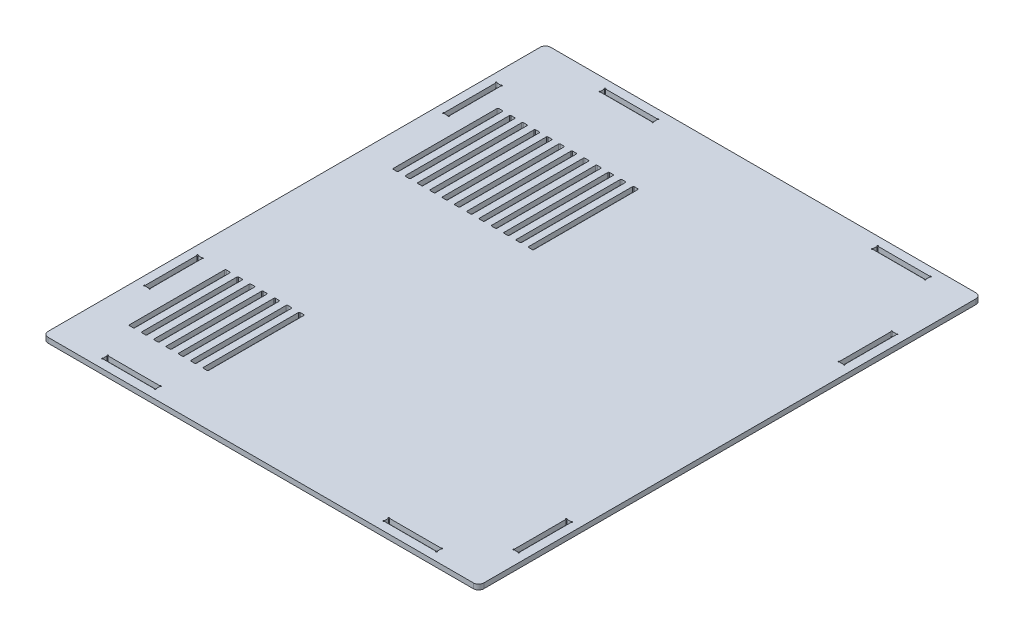
SolidWorks part; units mm, degrees
material "Acrylic (Medium-high impact)"
ref_plane "Front Plane" through (0, 0, 0) normal (0, 0, 1) x (1, 0, 0)
ref_plane "Top Plane" through (0, 0, 0) normal (0, 1, 0) x (1, 0, 0)
ref_plane "Right Plane" through (0, 0, 0) normal (1, 0, 0) x (0, 0, -1)
ref_plane "Plane1" through (0, 81.9, 0) normal (0, 1, 0) x (1, 0, 0)
sketch "Sketch1" plane through (0, 81.9, 0) normal (0, 1, 0) x (1, 0, 0)
  line L0 (-120.9, -142.9) -> (120.9, -142.9)
  line L1 (123.9, -139.9) -> (123.9, 139.9)
  line L2 (120.9, 142.9) -> (-120.9, 142.9)
  line L3 (-123.9, 139.9) -> (-123.9, -139.9)
  line L4 (-94.6875, -137.95) -> (-65.3125, -137.95)
  line L5 (-64.9625, -137.6) -> (-64.9625, -135.3)
  line L6 (-65.3125, -134.95) -> (-94.6875, -134.95)
  line L7 (-95.0375, -135.3) -> (-95.0375, -137.6)
  line L8 (65.3125, -137.95) -> (94.6875, -137.95)
  line L9 (95.0375, -137.6) -> (95.0375, -135.3)
  line L10 (94.6875, -134.95) -> (65.3125, -134.95)
  line L11 (64.9625, -135.3) -> (64.9625, -137.6)
  line L12 (-84.6875, 134.95) -> (-55.3125, 134.95)
  line L13 (-54.9625, 135.3) -> (-54.9625, 137.6)
  line L14 (-55.3125, 137.95) -> (-84.6875, 137.95)
  line L15 (-85.0375, 137.6) -> (-85.0375, 135.3)
  line L16 (70.3125, 134.95) -> (99.6875, 134.95)
  line L17 (100.0375, 135.3) -> (100.0375, 137.6)
  line L18 (99.6875, 137.95) -> (70.3125, 137.95)
  line L19 (69.9625, 137.6) -> (69.9625, 135.3)
  line L20 (116.3, -115.0375) -> (118.6, -115.0375)
  line L21 (118.95, -114.6875) -> (118.95, -85.3125)
  line L22 (118.6, -84.9625) -> (116.3, -84.9625)
  line L23 (115.95, -85.3125) -> (115.95, -114.6875)
  line L24 (116.3, 69.9625) -> (118.6, 69.9625)
  line L25 (118.95, 70.3125) -> (118.95, 99.6875)
  line L26 (118.6, 100.0375) -> (116.3, 100.0375)
  line L27 (115.95, 99.6875) -> (115.95, 70.3125)
  line L28 (-118.6, -90.0375) -> (-116.3, -90.0375)
  line L29 (-115.95, -89.6875) -> (-115.95, -60.3125)
  line L30 (-116.3, -59.9625) -> (-118.6, -59.9625)
  line L31 (-118.95, -60.3125) -> (-118.95, -89.6875)
  line L32 (-118.6, 79.9625) -> (-116.3, 79.9625)
  line L33 (-115.95, 80.3125) -> (-115.95, 109.6875)
  line L34 (-116.3, 110.0375) -> (-118.6, 110.0375)
  line L35 (-118.95, 109.6875) -> (-118.95, 80.3125)
  line L36 (-103.5, -114) -> (-101.5, -114)
  line L37 (-101, -113.5) -> (-101, -59.5)
  line L38 (-101.5, -59) -> (-103.5, -59)
  line L39 (-104, -59.5) -> (-104, -113.5)
  line L40 (-96.5, -114) -> (-94.5, -114)
  line L41 (-94, -113.5) -> (-94, -59.5)
  line L42 (-94.5, -59) -> (-96.5, -59)
  line L43 (-97, -59.5) -> (-97, -113.5)
  line L44 (-89.5, -114) -> (-87.5, -114)
  line L45 (-87, -113.5) -> (-87, -59.5)
  line L46 (-87.5, -59) -> (-89.5, -59)
  line L47 (-90, -59.5) -> (-90, -113.5)
  line L48 (-82.5, -114) -> (-80.5, -114)
  line L49 (-80, -113.5) -> (-80, -59.5)
  line L50 (-80.5, -59) -> (-82.5, -59)
  line L51 (-83, -59.5) -> (-83, -113.5)
  line L52 (-75.5, -114) -> (-73.5, -114)
  line L53 (-73, -113.5) -> (-73, -59.5)
  line L54 (-73.5, -59) -> (-75.5, -59)
  line L55 (-76, -59.5) -> (-76, -113.5)
  line L56 (-68.5, -114) -> (-66.5, -114)
  line L57 (-66, -113.5) -> (-66, -59.5)
  line L58 (-66.5, -59) -> (-68.5, -59)
  line L59 (-69, -59.5) -> (-69, -113.5)
  line L60 (-61.5, -114) -> (-59.5, -114)
  line L61 (-59, -113.5) -> (-59, -59.5)
  line L62 (-59.5, -59) -> (-61.5, -59)
  line L63 (-62, -59.5) -> (-62, -113.5)
  line L64 (-105.5, 38) -> (-103.5, 38)
  line L65 (-103, 38.5) -> (-103, 97.5)
  line L66 (-103.5, 98) -> (-105.5, 98)
  line L67 (-106, 97.5) -> (-106, 38.5)
  line L68 (-98.5, 38) -> (-96.5, 38)
  line L69 (-96, 38.5) -> (-96, 97.5)
  line L70 (-96.5, 98) -> (-98.5, 98)
  line L71 (-99, 97.5) -> (-99, 38.5)
  line L72 (-91.5, 38) -> (-89.5, 38)
  line L73 (-89, 38.5) -> (-89, 97.5)
  line L74 (-89.5, 98) -> (-91.5, 98)
  line L75 (-92, 97.5) -> (-92, 38.5)
  line L76 (-84.5, 38) -> (-82.5, 38)
  line L77 (-82, 38.5) -> (-82, 97.5)
  line L78 (-82.5, 98) -> (-84.5, 98)
  line L79 (-85, 97.5) -> (-85, 38.5)
  line L80 (-77.5, 38) -> (-75.5, 38)
  line L81 (-75, 38.5) -> (-75, 97.5)
  line L82 (-75.5, 98) -> (-77.5, 98)
  line L83 (-78, 97.5) -> (-78, 38.5)
  line L84 (-70.5, 38) -> (-68.5, 38)
  line L85 (-68, 38.5) -> (-68, 97.5)
  line L86 (-68.5, 98) -> (-70.5, 98)
  line L87 (-71, 97.5) -> (-71, 38.5)
  line L88 (-63.5, 38) -> (-61.5, 38)
  line L89 (-61, 38.5) -> (-61, 97.5)
  line L90 (-61.5, 98) -> (-63.5, 98)
  line L91 (-64, 97.5) -> (-64, 38.5)
  line L92 (-56.5, 38) -> (-54.5, 38)
  line L93 (-54, 38.5) -> (-54, 97.5)
  line L94 (-54.5, 98) -> (-56.5, 98)
  line L95 (-57, 97.5) -> (-57, 38.5)
  line L96 (-49.5, 38) -> (-47.5, 38)
  line L97 (-47, 38.5) -> (-47, 97.5)
  line L98 (-47.5, 98) -> (-49.5, 98)
  line L99 (-50, 97.5) -> (-50, 38.5)
  line L100 (-42.5, 38) -> (-40.5, 38)
  line L101 (-40, 38.5) -> (-40, 97.5)
  line L102 (-40.5, 98) -> (-42.5, 98)
  line L103 (-43, 97.5) -> (-43, 38.5)
  line L104 (-35.5, 38) -> (-33.5, 38)
  line L105 (-33, 38.5) -> (-33, 97.5)
  line L106 (-33.5, 98) -> (-35.5, 98)
  line L107 (-36, 97.5) -> (-36, 38.5)
  line L108 (-28.5, 38) -> (-26.5, 38)
  line L109 (-26, 38.5) -> (-26, 97.5)
  line L110 (-26.5, 98) -> (-28.5, 98)
  line L111 (-29, 97.5) -> (-29, 38.5)
  arc A0 (-123.9, -139.9) -> (-120.9, -142.9) centre (-120.9, -139.9) ccw
  arc A1 (120.9, -142.9) -> (123.9, -139.9) centre (120.9, -139.9) ccw
  arc A2 (123.9, 139.9) -> (120.9, 142.9) centre (120.9, 139.9) ccw
  arc A3 (-120.9, 142.9) -> (-123.9, 139.9) centre (-120.9, 139.9) ccw
  arc A4 (-65.3125, -137.95) -> (-64.9625, -137.6) centre (-64.9625, -137.95) ccw
  arc A5 (-64.9625, -135.3) -> (-65.3125, -134.95) centre (-64.9625, -134.95) ccw
  arc A6 (-94.6875, -134.95) -> (-95.0375, -135.3) centre (-95.0375, -134.95) ccw
  arc A7 (-95.0375, -137.6) -> (-94.6875, -137.95) centre (-95.0375, -137.95) ccw
  arc A8 (94.6875, -137.95) -> (95.0375, -137.6) centre (95.0375, -137.95) ccw
  arc A9 (95.0375, -135.3) -> (94.6875, -134.95) centre (95.0375, -134.95) ccw
  arc A10 (65.3125, -134.95) -> (64.9625, -135.3) centre (64.9625, -134.95) ccw
  arc A11 (64.9625, -137.6) -> (65.3125, -137.95) centre (64.9625, -137.95) ccw
  arc A12 (-55.3125, 134.95) -> (-54.9625, 135.3) centre (-54.9625, 134.95) ccw
  arc A13 (-54.9625, 137.6) -> (-55.3125, 137.95) centre (-54.9625, 137.95) ccw
  arc A14 (-84.6875, 137.95) -> (-85.0375, 137.6) centre (-85.0375, 137.95) ccw
  arc A15 (-85.0375, 135.3) -> (-84.6875, 134.95) centre (-85.0375, 134.95) ccw
  arc A16 (99.6875, 134.95) -> (100.0375, 135.3) centre (100.0375, 134.95) ccw
  arc A17 (100.0375, 137.6) -> (99.6875, 137.95) centre (100.0375, 137.95) ccw
  arc A18 (70.3125, 137.95) -> (69.9625, 137.6) centre (69.9625, 137.95) ccw
  arc A19 (69.9625, 135.3) -> (70.3125, 134.95) centre (69.9625, 134.95) ccw
  arc A20 (118.6, -115.0375) -> (118.95, -114.6875) centre (118.95, -115.0375) ccw
  arc A21 (118.95, -85.3125) -> (118.6, -84.9625) centre (118.95, -84.9625) ccw
  arc A22 (116.3, -84.9625) -> (115.95, -85.3125) centre (115.95, -84.9625) ccw
  arc A23 (115.95, -114.6875) -> (116.3, -115.0375) centre (115.95, -115.0375) ccw
  arc A24 (118.6, 69.9625) -> (118.95, 70.3125) centre (118.95, 69.9625) ccw
  arc A25 (118.95, 99.6875) -> (118.6, 100.0375) centre (118.95, 100.0375) ccw
  arc A26 (116.3, 100.0375) -> (115.95, 99.6875) centre (115.95, 100.0375) ccw
  arc A27 (115.95, 70.3125) -> (116.3, 69.9625) centre (115.95, 69.9625) ccw
  arc A28 (-116.3, -90.0375) -> (-115.95, -89.6875) centre (-115.95, -90.0375) ccw
  arc A29 (-115.95, -60.3125) -> (-116.3, -59.9625) centre (-115.95, -59.9625) ccw
  arc A30 (-118.6, -59.9625) -> (-118.95, -60.3125) centre (-118.95, -59.9625) ccw
  arc A31 (-118.95, -89.6875) -> (-118.6, -90.0375) centre (-118.95, -90.0375) ccw
  arc A32 (-116.3, 79.9625) -> (-115.95, 80.3125) centre (-115.95, 79.9625) ccw
  arc A33 (-115.95, 109.6875) -> (-116.3, 110.0375) centre (-115.95, 110.0375) ccw
  arc A34 (-118.6, 110.0375) -> (-118.95, 109.6875) centre (-118.95, 110.0375) ccw
  arc A35 (-118.95, 80.3125) -> (-118.6, 79.9625) centre (-118.95, 79.9625) ccw
  arc A36 (-104, -113.5) -> (-103.5, -114) centre (-103.5, -113.5) ccw
  arc A37 (-101.5, -114) -> (-101, -113.5) centre (-101.5, -113.5) ccw
  arc A38 (-101, -59.5) -> (-101.5, -59) centre (-101.5, -59.5) ccw
  arc A39 (-103.5, -59) -> (-104, -59.5) centre (-103.5, -59.5) ccw
  arc A40 (-97, -113.5) -> (-96.5, -114) centre (-96.5, -113.5) ccw
  arc A41 (-94.5, -114) -> (-94, -113.5) centre (-94.5, -113.5) ccw
  arc A42 (-94, -59.5) -> (-94.5, -59) centre (-94.5, -59.5) ccw
  arc A43 (-96.5, -59) -> (-97, -59.5) centre (-96.5, -59.5) ccw
  arc A44 (-90, -113.5) -> (-89.5, -114) centre (-89.5, -113.5) ccw
  arc A45 (-87.5, -114) -> (-87, -113.5) centre (-87.5, -113.5) ccw
  arc A46 (-87, -59.5) -> (-87.5, -59) centre (-87.5, -59.5) ccw
  arc A47 (-89.5, -59) -> (-90, -59.5) centre (-89.5, -59.5) ccw
  arc A48 (-83, -113.5) -> (-82.5, -114) centre (-82.5, -113.5) ccw
  arc A49 (-80.5, -114) -> (-80, -113.5) centre (-80.5, -113.5) ccw
  arc A50 (-80, -59.5) -> (-80.5, -59) centre (-80.5, -59.5) ccw
  arc A51 (-82.5, -59) -> (-83, -59.5) centre (-82.5, -59.5) ccw
  arc A52 (-76, -113.5) -> (-75.5, -114) centre (-75.5, -113.5) ccw
  arc A53 (-73.5, -114) -> (-73, -113.5) centre (-73.5, -113.5) ccw
  arc A54 (-73, -59.5) -> (-73.5, -59) centre (-73.5, -59.5) ccw
  arc A55 (-75.5, -59) -> (-76, -59.5) centre (-75.5, -59.5) ccw
  arc A56 (-69, -113.5) -> (-68.5, -114) centre (-68.5, -113.5) ccw
  arc A57 (-66.5, -114) -> (-66, -113.5) centre (-66.5, -113.5) ccw
  arc A58 (-66, -59.5) -> (-66.5, -59) centre (-66.5, -59.5) ccw
  arc A59 (-68.5, -59) -> (-69, -59.5) centre (-68.5, -59.5) ccw
  arc A60 (-62, -113.5) -> (-61.5, -114) centre (-61.5, -113.5) ccw
  arc A61 (-59.5, -114) -> (-59, -113.5) centre (-59.5, -113.5) ccw
  arc A62 (-59, -59.5) -> (-59.5, -59) centre (-59.5, -59.5) ccw
  arc A63 (-61.5, -59) -> (-62, -59.5) centre (-61.5, -59.5) ccw
  arc A64 (-106, 38.5) -> (-105.5, 38) centre (-105.5, 38.5) ccw
  arc A65 (-103.5, 38) -> (-103, 38.5) centre (-103.5, 38.5) ccw
  arc A66 (-103, 97.5) -> (-103.5, 98) centre (-103.5, 97.5) ccw
  arc A67 (-105.5, 98) -> (-106, 97.5) centre (-105.5, 97.5) ccw
  arc A68 (-99, 38.5) -> (-98.5, 38) centre (-98.5, 38.5) ccw
  arc A69 (-96.5, 38) -> (-96, 38.5) centre (-96.5, 38.5) ccw
  arc A70 (-96, 97.5) -> (-96.5, 98) centre (-96.5, 97.5) ccw
  arc A71 (-98.5, 98) -> (-99, 97.5) centre (-98.5, 97.5) ccw
  arc A72 (-92, 38.5) -> (-91.5, 38) centre (-91.5, 38.5) ccw
  arc A73 (-89.5, 38) -> (-89, 38.5) centre (-89.5, 38.5) ccw
  arc A74 (-89, 97.5) -> (-89.5, 98) centre (-89.5, 97.5) ccw
  arc A75 (-91.5, 98) -> (-92, 97.5) centre (-91.5, 97.5) ccw
  arc A76 (-85, 38.5) -> (-84.5, 38) centre (-84.5, 38.5) ccw
  arc A77 (-82.5, 38) -> (-82, 38.5) centre (-82.5, 38.5) ccw
  arc A78 (-82, 97.5) -> (-82.5, 98) centre (-82.5, 97.5) ccw
  arc A79 (-84.5, 98) -> (-85, 97.5) centre (-84.5, 97.5) ccw
  arc A80 (-78, 38.5) -> (-77.5, 38) centre (-77.5, 38.5) ccw
  arc A81 (-75.5, 38) -> (-75, 38.5) centre (-75.5, 38.5) ccw
  arc A82 (-75, 97.5) -> (-75.5, 98) centre (-75.5, 97.5) ccw
  arc A83 (-77.5, 98) -> (-78, 97.5) centre (-77.5, 97.5) ccw
  arc A84 (-71, 38.5) -> (-70.5, 38) centre (-70.5, 38.5) ccw
  arc A85 (-68.5, 38) -> (-68, 38.5) centre (-68.5, 38.5) ccw
  arc A86 (-68, 97.5) -> (-68.5, 98) centre (-68.5, 97.5) ccw
  arc A87 (-70.5, 98) -> (-71, 97.5) centre (-70.5, 97.5) ccw
  arc A88 (-64, 38.5) -> (-63.5, 38) centre (-63.5, 38.5) ccw
  arc A89 (-61.5, 38) -> (-61, 38.5) centre (-61.5, 38.5) ccw
  arc A90 (-61, 97.5) -> (-61.5, 98) centre (-61.5, 97.5) ccw
  arc A91 (-63.5, 98) -> (-64, 97.5) centre (-63.5, 97.5) ccw
  arc A92 (-57, 38.5) -> (-56.5, 38) centre (-56.5, 38.5) ccw
  arc A93 (-54.5, 38) -> (-54, 38.5) centre (-54.5, 38.5) ccw
  arc A94 (-54, 97.5) -> (-54.5, 98) centre (-54.5, 97.5) ccw
  arc A95 (-56.5, 98) -> (-57, 97.5) centre (-56.5, 97.5) ccw
  arc A96 (-50, 38.5) -> (-49.5, 38) centre (-49.5, 38.5) ccw
  arc A97 (-47.5, 38) -> (-47, 38.5) centre (-47.5, 38.5) ccw
  arc A98 (-47, 97.5) -> (-47.5, 98) centre (-47.5, 97.5) ccw
  arc A99 (-49.5, 98) -> (-50, 97.5) centre (-49.5, 97.5) ccw
  arc A100 (-43, 38.5) -> (-42.5, 38) centre (-42.5, 38.5) ccw
  arc A101 (-40.5, 38) -> (-40, 38.5) centre (-40.5, 38.5) ccw
  arc A102 (-40, 97.5) -> (-40.5, 98) centre (-40.5, 97.5) ccw
  arc A103 (-42.5, 98) -> (-43, 97.5) centre (-42.5, 97.5) ccw
  arc A104 (-36, 38.5) -> (-35.5, 38) centre (-35.5, 38.5) ccw
  arc A105 (-33.5, 38) -> (-33, 38.5) centre (-33.5, 38.5) ccw
  arc A106 (-33, 97.5) -> (-33.5, 98) centre (-33.5, 97.5) ccw
  arc A107 (-35.5, 98) -> (-36, 97.5) centre (-35.5, 97.5) ccw
  arc A108 (-29, 38.5) -> (-28.5, 38) centre (-28.5, 38.5) ccw
  arc A109 (-26.5, 38) -> (-26, 38.5) centre (-26.5, 38.5) ccw
  arc A110 (-26, 97.5) -> (-26.5, 98) centre (-26.5, 97.5) ccw
  arc A111 (-28.5, 98) -> (-29, 97.5) centre (-28.5, 97.5) ccw
extrude "Boss-Extrude1" add sketch "Sketch1" along normal blind 2.9
